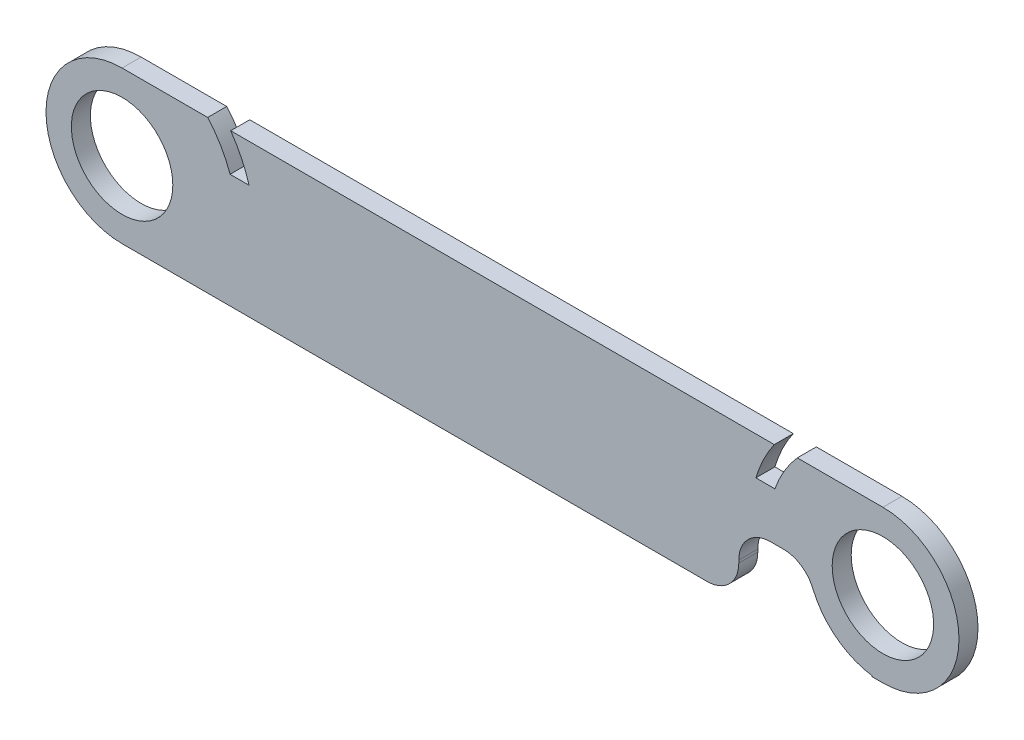
SolidWorks part; units mm, degrees
ref_plane "Front Plane" through (0, 0, 0) normal (0, 0, 1) x (1, 0, 0)
ref_plane "Top Plane" through (0, 0, 0) normal (0, 1, 0) x (1, 0, 0)
ref_plane "Right Plane" through (0, 0, 0) normal (1, 0, 0) x (0, 0, -1)
sketch "Sketch1" plane through (0, 0, 0) normal (0, 0, 1) x (1, 0, 0)
  line L0 (0, 0) -> (-120, 0) construction
  line L1 (0, -12) -> (-120, -12)
  line L2 (0, 12) -> (-120, 12)
  line L3 (-60, 54.1121) -> (-60, -43.0383) construction
  arc A0 (0, -12) -> (0, 12) centre (0, 0) ccw
  arc A1 (-120, 12) -> (-120, -12) centre (-120, 0) ccw
  circle A2 centre (-120, 0) radius 8
  circle A3 centre (0, 0) radius 8
  point P3 (-60, 0)
  dimension "D1" = 12
  dimension "D2" = 16
  dimension "D3" = 120
extrude "Boss-Extrude1" add sketch "Sketch1" along normal blind 3
sketch "Sketch2" plane through (0, 0, 3) normal (0, 0, 1) x (1, 0, 0)
  line L5 (-60, 60.961) -> (-60, -60.8124) construction
  line L6 (-120, -12) -> (0, -12) construction
  line L11 (0, 12) -> (-120, 12) construction
  line L14 (-17.0367, 6) -> (-20.0367, 6)
  line L15 (-13.5, 12) -> (-17.131, 12)
  line L16 (-102.9633, 6) -> (-99.9633, 6)
  line L17 (-106.5, 12) -> (-102.869, 12)
  arc A1 (-120, 12) -> (-120, -12) centre (-120, 0) ccw construction
  arc A2 (0, -12) -> (0, 12) centre (0, 0) ccw construction
  arc A3 (-13.5, 12) -> (-17.0367, 6) centre (0, 0) ccw
  arc A4 (-17.131, 12) -> (-20.0367, 6) centre (0, 0) ccw
  arc A5 (-102.869, 12) -> (-99.9633, 6) centre (-120, 0) cw
  arc A6 (-106.5, 12) -> (-102.9633, 6) centre (-120, 0) cw
  dimension "D2" = 3
  dimension "D3" = 18
  dimension "D1" = 13.5
extrude "Cut-Extrude1" cut sketch "Sketch2" against normal through all
sketch "Sketch5" plane through (0, 0, 3) normal (0, 0, 1) x (1, 0, 0)
  line L0 (-1.7312, -11.8583) -> (-1.7312, -12)
  line L1 (-120, -12) -> (0, -12) construction
  line L2 (-1.7312, -12) -> (-22.7312, -12)
  line L3 (-22.7312, -12) -> (-22.7312, -2.3442)
  line L4 (-22.7312, -1.5722) -> (-11.8805, -1.5722)
  line L5 (-22.7312, -1.5722) -> (-22.7312, -2.3442)
  arc A0 (-11.8805, -1.5722) -> (-1.7312, -11.8583) centre (0, 0) ccw
  dimension "D1" = 21
extrude "Cut-Extrude8" cut sketch "Sketch5" against normal blind 10
fillet "Fillet2" radius 5 1 edges at (-22.7312, -1.5722, 1.5)
fillet "Fillet3" radius 5 1 edges at (-11.8805, -1.5722, 1.5)
fillet "Fillet4" radius 5 1 edges at (-22.7312, -12, 1.5)
